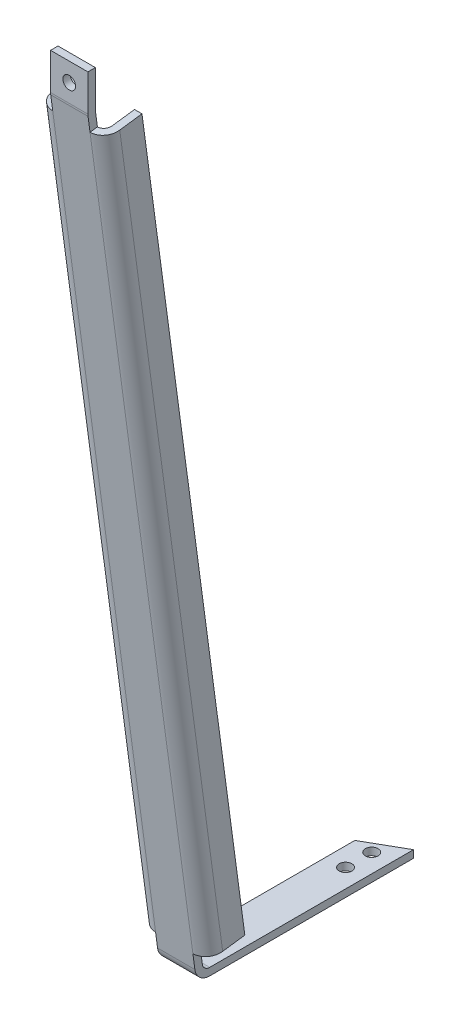
SolidWorks part; units mm, degrees
other "Roof Support Arm 1 Left"
ref_plane "Front Plane" through (0, 0, 0) normal (0, 0, 1) x (1, 0, 0)
ref_plane "Top Plane" through (0, 0, 0) normal (0, 1, 0) x (1, 0, 0)
ref_plane "Right Plane" through (0, 0, 0) normal (1, 0, 0) x (0, 0, -1)
sketch3d "Formed Web Section Sketch datum points"
  point P0 (-260, 0, 0)
  point P1 (-260, 10, 0)
  point P2 (-260, 0, 10)
ref_plane "Formed Web Section Sketch plane" through (-260, 0, 0) normal (1, 0, 0) x (0, 0, -1)
sketch "Formed Web Section Sketch" plane through (-260, 0, 0) normal (1, 0, 0) x (0, 0, -1)
  line L0 (-22, 64) -> (-77.3775, 64)
  line L1 (-81.3416, 67.4653) -> (-109.9641, 279.6667)
  line L2 (-110, 280.2014) -> (-110, 290)
  line L3 (-110, 290) -> (-108, 290)
  line L4 (-108, 290) -> (-108, 280.2014)
  line L5 (-107.9821, 279.9341) -> (-79.3595, 67.7327)
  line L6 (-77.3775, 66) -> (-22, 66)
  line L7 (-22, 66) -> (-22, 64)
  arc A0 (-81.3416, 67.4653) -> (-77.3775, 64) centre (-77.3775, 68) ccw
  arc A1 (-110, 280.2014) -> (-109.9641, 279.6667) centre (-106, 280.2014) ccw
  arc A2 (-108, 280.2014) -> (-107.9821, 279.9341) centre (-106, 280.2014) ccw
  arc A3 (-79.3595, 67.7327) -> (-77.3775, 66) centre (-77.3775, 68) ccw
extrude "Formed Web" add sketch "Formed Web Section Sketch" along normal blind 10 separate body
sketch3d "Edge Lip Sketch datum points"
  point P0 (-255, 71.5631, 80.8853)
  point P1 (-245, 71.5631, 80.8853)
  point P2 (-255, 70.2264, 90.7955)
ref_plane "Edge Lip Sketch plane" through (0, 80.9995, 10.9255) normal (0, -0.991, -0.1337) x (-1, 0, 0)
sketch "Edge Lip Sketch" plane through (0, 80.9995, 10.9255) normal (0, -0.991, -0.1337) x (-1, 0, 0)
  line L0 (264, -67.5933) -> (264, -61.5933)
  line L1 (264, -61.5933) -> (262, -61.5933)
  line L2 (262, -61.5933) -> (262, -67.5933)
  line L3 (260, -69.5933) -> (259.9, -69.5933)
  line L4 (259.9, -69.5933) -> (259.9, -71.5933)
  line L5 (259.9, -71.5933) -> (260, -71.5933)
  line L6 (246, -67.5933) -> (246, -61.5933)
  line L7 (246, -61.5933) -> (248, -61.5933)
  line L8 (248, -61.5933) -> (248, -67.5933)
  line L9 (250, -69.5933) -> (250.1, -69.5933)
  line L10 (250.1, -69.5933) -> (250.1, -71.5933)
  line L11 (250.1, -71.5933) -> (250, -71.5933)
  arc A0 (260, -71.5933) -> (264, -67.5933) centre (260, -67.5933) ccw
  arc A1 (260, -69.5933) -> (262, -67.5933) centre (260, -67.5933) ccw
  arc A2 (246, -67.5933) -> (250, -71.5933) centre (250, -67.5933) ccw
  arc A3 (248, -67.5933) -> (250, -69.5933) centre (250, -67.5933) ccw
extrude "Edge Stiffening Lips" add sketch "Edge Lip Sketch" against normal blind 206.1231
sketch3d "Wall Mount Hole Sketch datum points"
  point P0 (0, 63.8, 0)
  point P1 (10, 63.8, 0)
  point P2 (0, 63.8, 10)
ref_plane "Wall Mount Hole Sketch plane" through (0, 63.8, 0) normal (0, -1, 0) x (-1, 0, 0)
sketch "Wall Mount Hole Sketch" plane through (0, 63.8, 0) normal (0, -1, 0) x (-1, 0, 0)
  circle A0 centre (255, -29) radius 1.7
  circle A1 centre (255, -36) radius 1.7
extrude "Wall Mount Holes" cut sketch "Wall Mount Hole Sketch" against normal blind 2.4
sketch3d "Cover Mount Hole Sketch datum points"
  point P0 (0, 0, 107.8)
  point P1 (10, 0, 107.8)
  point P2 (0, 10, 107.8)
ref_plane "Cover Mount Hole Sketch plane" through (0, 0, 107.8) normal (0, 0, 1) x (1, 0, 0)
sketch "Cover Mount Hole Sketch" plane through (0, 0, 107.8) normal (0, 0, 1) x (1, 0, 0)
  circle A0 centre (-255, 285) radius 1.7
extrude "Cover Mount Hole" cut sketch "Cover Mount Hole Sketch" along normal blind 2.4
sketch3d "Lower Edge Clearance Sketch datum points"
  point P0 (0, 63.8, 0)
  point P1 (10, 63.8, 0)
  point P2 (0, 63.8, 10)
ref_plane "Lower Edge Clearance Sketch plane" through (0, 63.8, 0) normal (0, -1, 0) x (-1, 0, 0)
sketch "Lower Edge Clearance Sketch" plane through (0, 63.8, 0) normal (0, -1, 0) x (-1, 0, 0)
  line L0 (261, -20) -> (249, -20)
  line L1 (249, -20) -> (249, -22.23)
  line L2 (249, -22.23) -> (261, -29.07)
  line L3 (261, -29.07) -> (261, -20)
extrude "Lower Edge Clearance" cut sketch "Lower Edge Clearance Sketch" against normal blind 2.4
